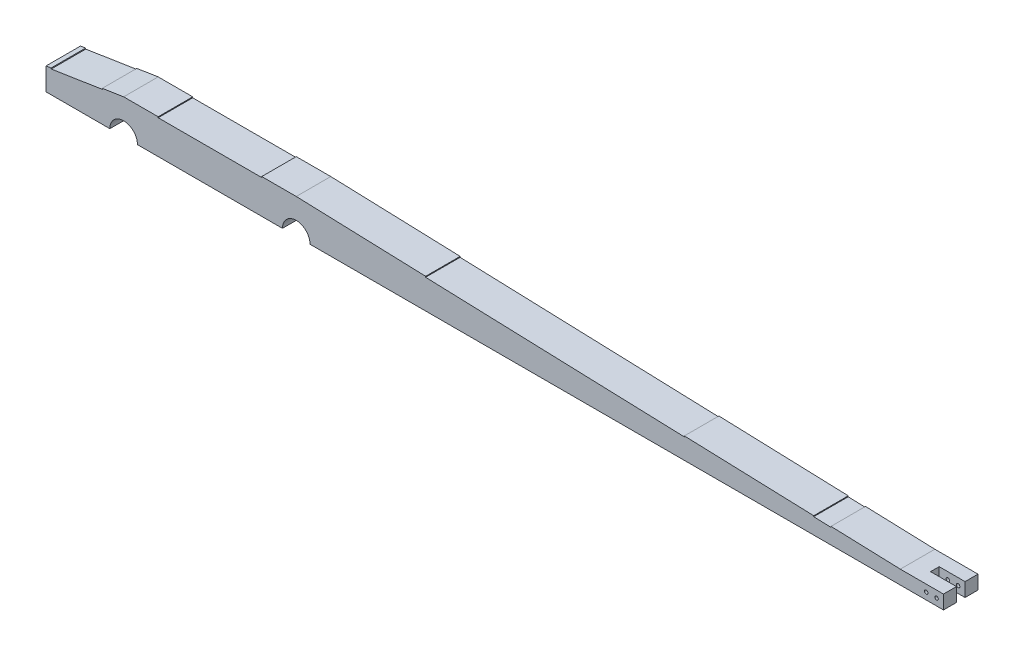
SolidWorks part; units mm, degrees
material "Mahogany"
ref_plane "Plan de face" through (0, 0, 0) normal (0, 0, 1) x (1, 0, 0)
ref_plane "Plan de dessus" through (0, 0, 0) normal (0, 1, 0) x (1, 0, 0)
ref_plane "Plan de droite" through (0, 0, 0) normal (1, 0, 0) x (0, 0, -1)
sketch "Sketch1" plane through (0, 0, 0) normal (0, 0, 1) x (1, 0, 0)
  line L0 (-8, 0) -> (-92, 0)
  line L1 (8, 0) -> (375, 0)
  line L2 (-108, 0) -> (-145, 0)
  line L3 (-100, 20) -> (0, 20)
  line L4 (0, 20) -> (350, 8)
  line L6 (-100, 20) -> (-145, 13)
  line L7 (-145, 0) -> (-145, 13)
  line L8 (350, 8) -> (375, 8)
  line L9 (375, 8) -> (375, 0)
  line L15 (-100, 0) -> (-100, 48.6354) construction
  line L16 (0, 0) -> (0, 46.3997) construction
  arc A0 (8, 0) -> (-8, 0) centre (0, 0) ccw
  arc A1 (-92, 0) -> (-108, 0) centre (-100, 0) ccw
  dimension "D6" = 8
  dimension "D7" = 520
  dimension "D11" = 8
  dimension "D1" = 100
  dimension "D2" = 45
  dimension "D4" = 8
  dimension "D5" = 20
  dimension "D9" = 7
  dimension "D12" = 350
extrude "Boss-Extrude1" add sketch "Sketch1" along normal blind 20
sketch "Sketch2" plane through (0.6849, 19.9765, 0) normal (0.0343, 0.9994, 0) x (0.9994, -0.0343, 0)
  line L0 (349.5203, 0) -> (-0.6853, 0) construction
  line L1 (74.3147, 0) -> (224.3147, 0)
  line L2 (74.3147, 0) -> (74.3147, -20)
  line L3 (74.3147, -20) -> (224.3147, -20)
  line L4 (224.3147, 0) -> (224.3147, -20)
  line L5 (349.5203, -20) -> (-0.6853, -20) construction
  line L6 (-0.6853, -20) -> (-0.6853, 0) construction
  line L8 (299.3147, 0) -> (309.3147, 0)
  line L9 (299.3147, 0) -> (299.3147, -20)
  line L10 (299.3147, -20) -> (309.3147, -20)
  line L11 (309.3147, 0) -> (309.3147, -20)
  dimension "D1" = 150
  dimension "D2" = 75
  dimension "D3" = 10
  dimension "D4" = 75
extrude "RopeGroove1" cut sketch "Sketch2" against normal blind 0.5
sketch "Sketch4" plane through (0, 20, 0) normal (0, 1, 0) x (1, 0, 0)
  line L0 (0, 0) -> (-100, 0) construction
  line L1 (-80, 0) -> (-20, 0)
  line L2 (-80, 0) -> (-80, -20)
  line L3 (-80, -20) -> (-20, -20)
  line L4 (-20, 0) -> (-20, -20)
  line L5 (0, -20) -> (-100, -20) construction
  line L6 (-50, -20) -> (-50, 0) construction
  point P10 (-50, -20)
  dimension "D1" = 60
extrude "RopeGroove2" cut sketch "Sketch4" against normal blind 0.5
sketch "Sketch5" plane through (-5.4002, 34.7155, 0) normal (-0.1537, 0.9881, 0) x (0.9881, 0.1537, 0)
  line L0 (-95.7375, 0) -> (-141.2787, 0) construction
  line L1 (-138.2787, 0) -> (-108.2787, 0)
  line L2 (-138.2787, 0) -> (-138.2787, -20)
  line L3 (-138.2787, -20) -> (-108.2787, -20)
  line L4 (-108.2787, 0) -> (-108.2787, -20)
  line L5 (-95.7375, -20) -> (-141.2787, -20) construction
  line L7 (-141.2787, -20) -> (-141.2787, 0) construction
  dimension "D1" = 30
  dimension "D2" = 3
extrude "RopeGroove3" cut sketch "Sketch5" against normal blind 0.5
sketch "Sketch6" plane through (0, 8, 0) normal (0, 1, 0) x (1, 0, 0)
  line L0 (375, -20) -> (375, 0) construction
  line L1 (360, -12.5) -> (375, -12.5)
  line L2 (360, -12.5) -> (360, -7.5)
  line L3 (360, -7.5) -> (375, -7.5)
  line L4 (375, -12.5) -> (375, -7.5)
  line L5 (360, -12.5) -> (375, -7.5) construction
  line L6 (360, -7.5) -> (375, -12.5) construction
  line L7 (350, -10) -> (375, -10) construction
  line L8 (350, -20) -> (350, 0) construction
  point P0 (367.5, -10)
  dimension "D1" = 5
  dimension "D2" = 15
extrude "Cut-Extrude1" cut sketch "Sketch6" against normal through all
sketch "Sketch7" plane through (0, 0, 20) normal (0, 0, 1) x (1, 0, 0)
  line L0 (375, 4) -> (360, 4) construction
  line L1 (375, 0) -> (375, 8) construction
  line L2 (360, 0) -> (360, 8) construction
  line L3 (360, 0) -> (360, 8)
  circle A0 centre (371, 4) radius 1
  circle A1 centre (365, 4) radius 1
  dimension "D1" = 2
  dimension "D2" = 2
  dimension "D3" = 4
  dimension "D4" = 5
extrude "Cut-Extrude2" cut sketch "Sketch7" against normal through all contours A1 L0 | L0 A1 | L0 A0 | A0 L0
